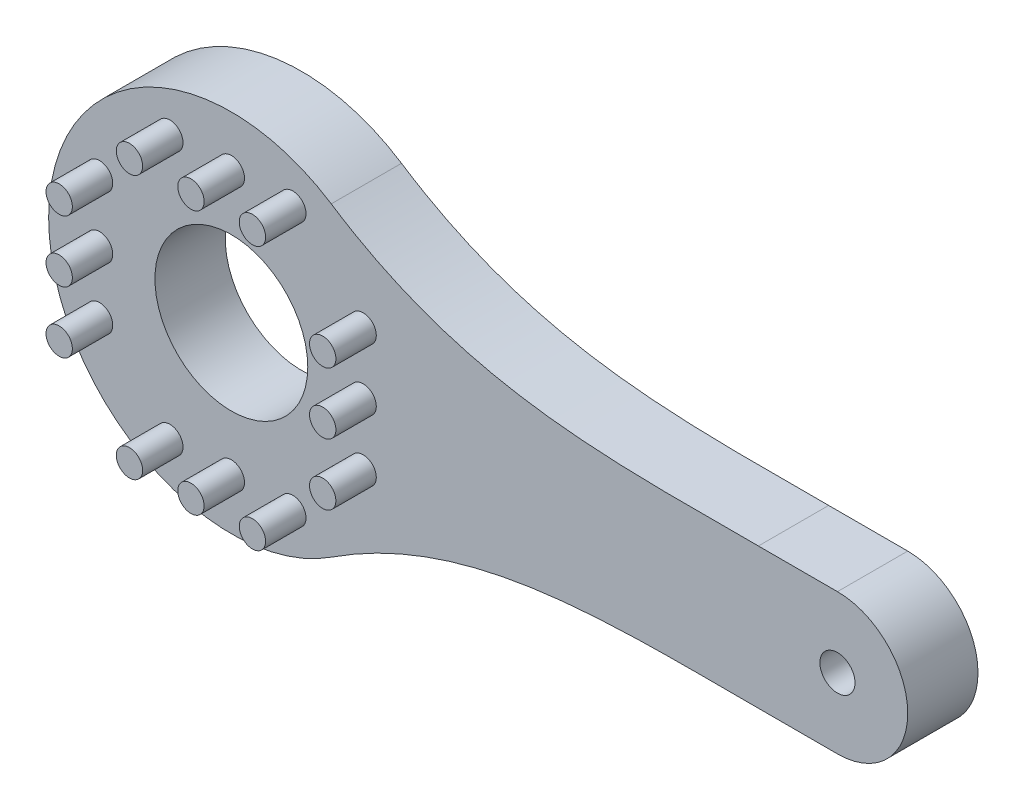
SolidWorks part; units mm, degrees
ref_plane "Front Plane" through (0, 0, 0) normal (0, 0, 1) x (1, 0, 0)
ref_plane "Top Plane" through (0, 0, 0) normal (0, 1, 0) x (1, 0, 0)
ref_plane "Right Plane" through (0, 0, 0) normal (1, 0, 0) x (0, 0, -1)
sketch "Sketch1" plane through (0, 0, 0) normal (0, 0, 1) x (1, 0, 0)
  line L0 (0, 0) -> (52.669, 0) construction
  line L1 (30, 4) -> (34.5, 4)
  line L2 (30, -4) -> (34.5, -4)
  arc A0 (5.6862, 8.7079) -> (5.6862, -8.7079) centre (0, 0) ccw
  circle A1 centre (0, 0) radius 4.35
  arc A2 (34.5, 4) -> (34.5, -4) centre (34.5, 0) cw
  circle A3 centre (34.5, 0) radius 1
  spline S0 degree 3 poles (5.6862, 8.7079) (13.4104, 3.664) (21.2669, 4) (30, 4) knots 0 0 0 0 1 1 1 1
  spline S1 degree 3 poles (5.6862, -8.7079) (13.4104, -3.664) (21.2669, -4) (30, -4) knots 0 0 0 0 1 1 1 1
  dimension "D1" = 20.8
  dimension "D2" = 8.7
  dimension "D8" = 34.5
  dimension "D7" = 2
  dimension "D3" = 4
  dimension "D4" = 4.5
  dimension "D5" = 17.1959
  dimension "D6" = 30
extrude "Boss-Extrude1" add sketch "Sketch1" along normal blind 4
sketch "Sketch2" plane through (0, 0, 4) normal (0, 0, 1) x (1, 0, 0)
  line L0 (0, -55) -> (0, 55) construction
  line L1 (55, 0) -> (-55, 0) construction
  circle A0 centre (0, 0) radius 10.4 construction
  circle A1 centre (0, 0) radius 4.35 construction
  circle A2 centre (0, 7.5) radius 0.75
  circle A3 centre (3.5, 7.5) radius 0.75
  circle A4 centre (-3.5, 7.5) radius 0.75
  circle A5 centre (3.5, -7.5) radius 0.75
  circle A6 centre (0, -7.5) radius 0.75
  circle A7 centre (-3.5, -7.5) radius 0.75
  circle A8 centre (7.5, 0) radius 0.75
  circle A9 centre (7.5, 3.5) radius 0.75
  circle A10 centre (7.5, -3.5) radius 0.75
  circle A11 centre (-7.5, -3.5) radius 0.75
  circle A12 centre (-7.5, 0) radius 0.75
  circle A13 centre (-7.5, 3.5) radius 0.75
  dimension "D1" = 20.8
  dimension "D2" = 8.7
  dimension "D3" = 1.5
  dimension "D5" = 1.5
  dimension "D9" = 1.5
  dimension "D12" = 1.5
  dimension "D4" = 7.5
  dimension "D6" = 3.5
  dimension "D7" = 0
  dimension "D8" = 0
  dimension "D10" = 7.5
  dimension "D11" = 0
  dimension "D13" = 3.5
  dimension "D14" = 0
extrude "Boss-Extrude2" add sketch "Sketch2" along normal blind 2.3
